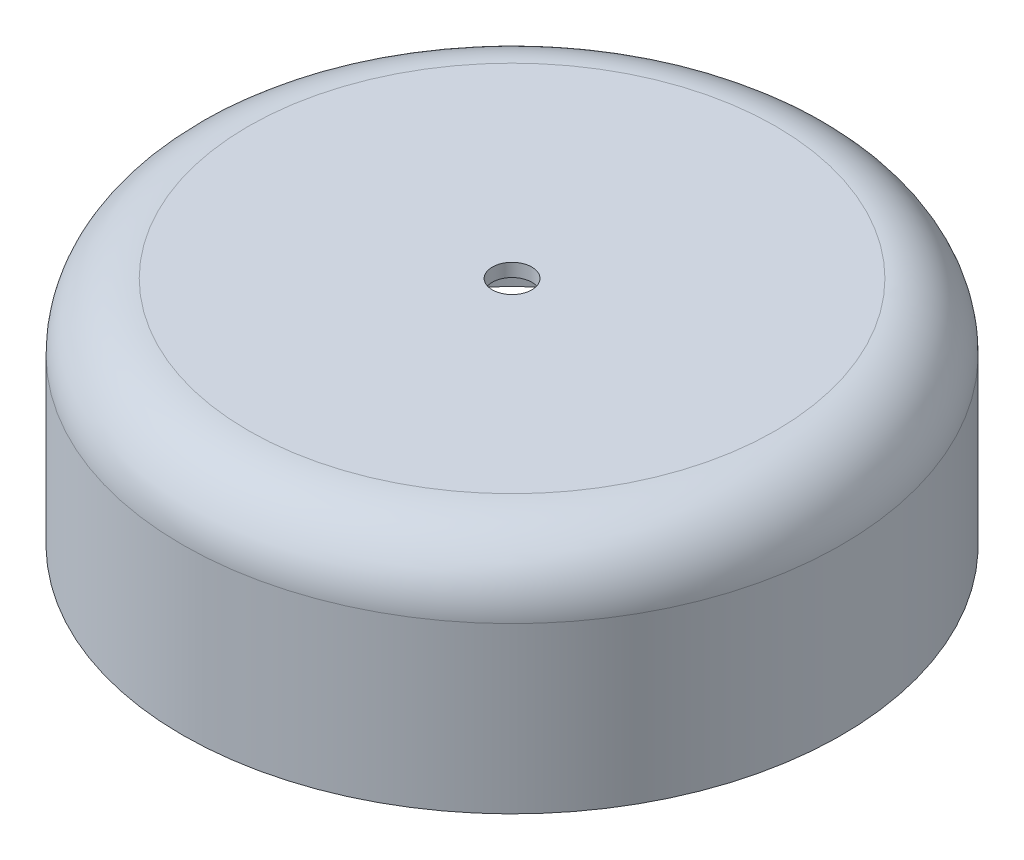
SolidWorks part; units mm, degrees
ref_plane "Front Plane" through (0, 0, 0) normal (0, 0, 1) x (1, 0, 0)
ref_plane "Top Plane" through (0, 0, 0) normal (0, 1, 0) x (1, 0, 0)
ref_plane "Right Plane" through (0, 0, 0) normal (1, 0, 0) x (0, 0, -1)
sketch "Sketch1" plane through (0, 0, 0) normal (0, 1, 0) x (1, 0, 0)
  circle A0 centre (0, 0) radius 50
  dimension "D1" = 100
extrude "Boss-Extrude1" add sketch "Sketch1" along normal blind 35
fillet "Fillet1" radius 10 1 edges at (0, 35, 50)
shell "Shell1" thickness 2
sketch "Sketch2" plane through (0, 33, 0) normal (0, -1, 0) x (1, 0, 0)
  line L0 (0, 55.9693) -> (0, -55.9693) construction
  line L2 (-6, 10.5) -> (6, 10.5)
  line L3 (-6, 10.5) -> (-6, 6)
  line L4 (-6, 6) -> (6, 6)
  line L5 (6, 10.5) -> (6, 6)
  line L6 (0, 6) -> (0, 10.5) construction
  line L7 (-6, 8.25) -> (6, 8.25) construction
  line L8 (-6, -17) -> (6, -17)
  line L9 (-6, -17) -> (-6, -21.5)
  line L10 (-6, -21.5) -> (6, -21.5)
  line L11 (6, -17) -> (6, -21.5)
  line L12 (0, -21.5) -> (0, -17) construction
  line L13 (-6, -19.25) -> (6, -19.25) construction
  point P0 (0, 8.25)
  point P5 (0, 0)
  point P10 (0, -19.25)
  dimension "D1" = 12
  dimension "D2" = 12
  dimension "D3" = 4.5
  dimension "D4" = 4.5
  dimension "D5" = 6
  dimension "D6" = 17
extrude "Boss-Extrude2" add sketch "Sketch2" along normal blind 6.5
sketch "Sketch3" plane through (0, 35, 0) normal (0, 1, 0) x (1, 0, 0)
  circle A0 centre (0, 0) radius 3
  dimension "D1" = 6
extrude "Cut-Extrude1" cut sketch "Sketch3" against normal blind 6.5
